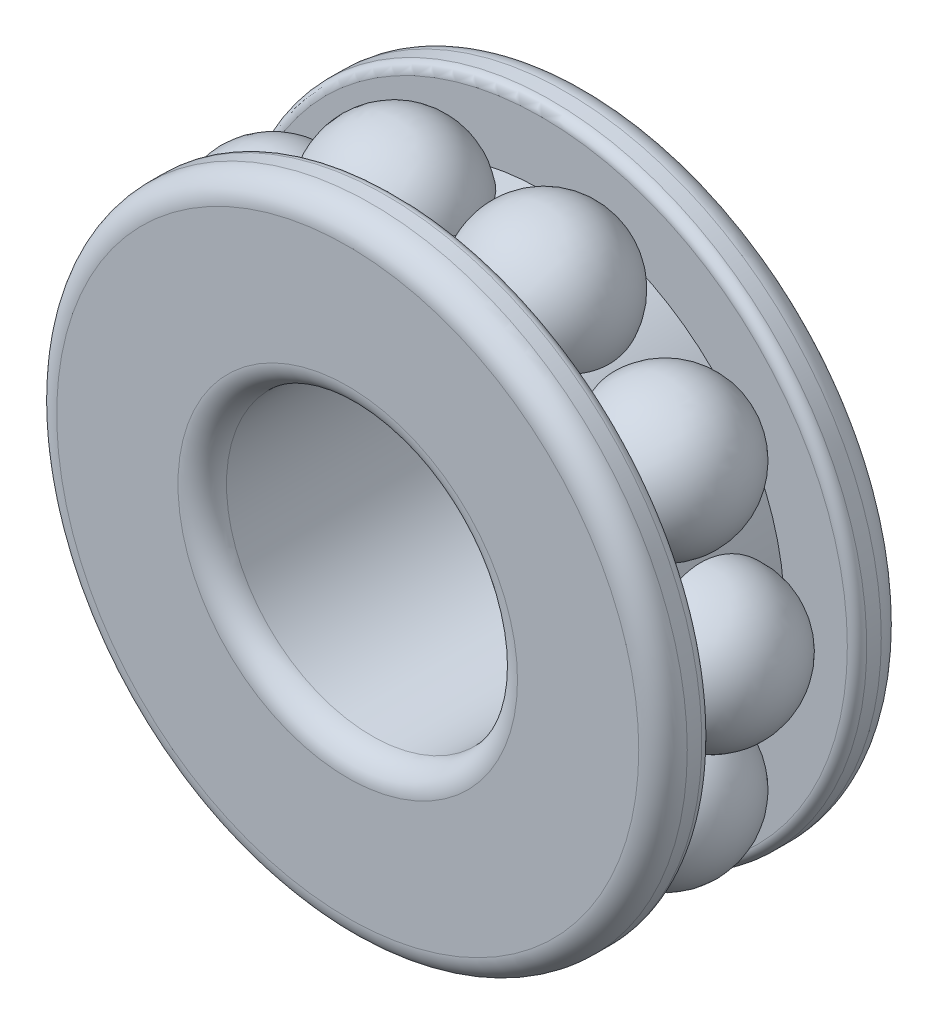
SolidWorks part; units mm, degrees
ref_plane "Ebene vorne" through (0, 0, 0) normal (0, 0, 1) x (1, 0, 0)
ref_plane "Ebene oben" through (0, 0, 0) normal (0, 1, 0) x (1, 0, 0)
ref_plane "Ebene rechts" through (0, 0, 0) normal (1, 0, 0) x (0, 0, -1)
sketch "Skizze1" plane through (0, 0, 0) normal (0, 0, 1) x (1, 0, 0)
  circle A0 centre (0, 0) radius 6.5
  circle A1 centre (0, 0) radius 3
extrude "Aufsatz-Linear austragen1" add sketch "Skizze1" along normal blind 5
fillet "Verrundung1" radius 0.5 4 edges at (3, 0, 0) (6.5, 0, 0) (3, 0, 5) (6.5, 0, 5)
ref_plane "Ebene1" through (0, 0, 2.5) normal (0, 0, -1) x (-1, 0, 0)
sketch "Skizze2" plane through (0, 0, 2.5) normal (0, 0, -1) x (-1, 0, 0)
  circle A0 centre (0, 0) radius 5
  circle A1 centre (0, 0) radius 8.2167
extrude "Schnitt-Linear austragen1" cut sketch "Skizze2" against normal blind 1.5 and the other way blind 1.5
sketch "Skizze3" plane through (0, 0, 2.5) normal (0, 0, -1) x (-1, 0, 0)
  line L0 (-5, 1.5) -> (-5, -1.5)
  arc A0 (-5, 1.5) -> (-5, -1.5) centre (-5, 0) ccw
  circle A1 centre (0, 0) radius 6.5 construction
  dimension "D1" = 5
revolve "Rotation1" add sketch "Skizze3" angle 360 about L0
pattern_circular "Kreismuster3" count 10 every 36 about axis through (0, 0, 0) along (0, 0, 1) of "Rotation1"
fillet "Verrundung2" radius 0.2 2 edges at (-6.5, 0, 1) (-6.5, 0, 4)
